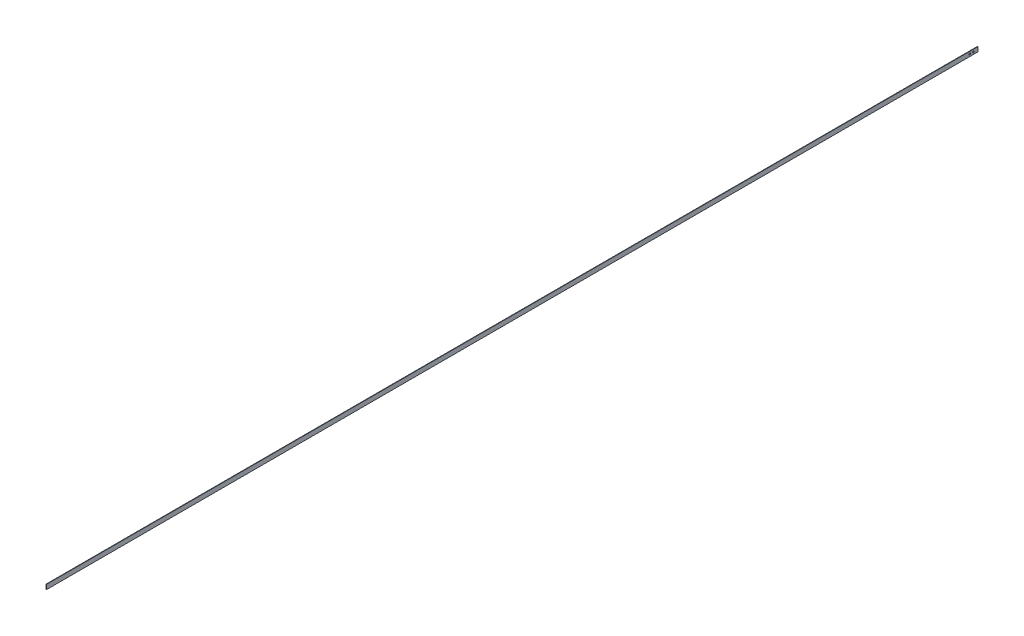
SolidWorks part; units mm, degrees
material "Bellirium COpper"
ref_plane "Front Plane" through (0, 0, 0) normal (0, 0, 1) x (1, 0, 0)
ref_plane "Top Plane" through (0, 0, 0) normal (0, 1, 0) x (1, 0, 0)
ref_plane "Right Plane" through (0, 0, 0) normal (1, 0, 0) x (0, 0, -1)
sketch "Sketch1" plane through (0, 0, 0) normal (0, 0, 1) x (1, 0, 0)
  line L1 (-0.15, -1.5) -> (0.15, -1.5)
  line L2 (-0.15, -1.5) -> (-0.15, 1.5)
  line L3 (-0.15, 1.5) -> (0.15, 1.5)
  line L4 (0.15, -1.5) -> (0.15, 1.5)
  line L5 (-0.15, -1.5) -> (0.15, 1.5) construction
  line L6 (-0.15, 1.5) -> (0.15, -1.5) construction
  point P0 (0, 0)
  dimension "D1" = 0.3
  dimension "D2" = 3
extrude "Boss-Extrude1" add sketch "Sketch1" along normal blind 610
hole_wizard "Ø1.0 (1) Diameter Hole1" positions "Sketch3" profile "Sketch2" hole size "Ø1.0" standard "ISO" end condition through all
sketch "Sketch3" plane through (0.15, 0, 0) normal (1, 0, 0) x (0, 0, -1)
  line L0 (0, 1.5) -> (0, -1.5) construction
  point P0 (-5.5, 0)
  point P2 (-3, 0)
  point P7 (-0.3486, 0.8734)
  dimension "D1" = 2.5
  dimension "D2" = 3
sketch "Sketch2" plane through (0.15, 0, 5.5) normal (0, 1, 0) x (0, 0, -1)
  line L0 (0, 0) -> (0, 0.3)
  line L1 (0, 0.3) -> (0.5, 0.3)
  line L2 (0.5, 0.3) -> (0.5, 0)
  line L5 (0.5, 0) -> (0, 0)
  line L11 (0, -6.35) -> (0, 107.95) construction
  dimension "Thru Hole Dia." = 1
  dimension "Thru Hole Depth" = 0.3
